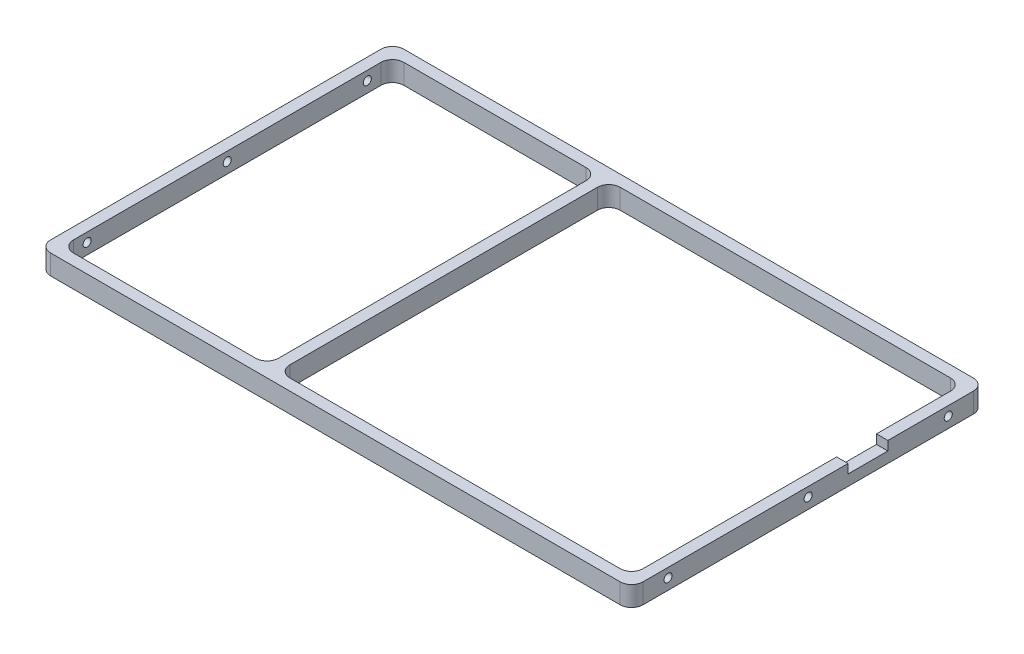
SolidWorks part; units mm, degrees
material "Delrin 2700 NC010, Low Viscosity Acetal Copolymer (SS)"
ref_plane "Front Plane" through (0, 0, 0) normal (0, 0, 1) x (1, 0, 0)
ref_plane "Top Plane" through (0, 0, 0) normal (0, 1, 0) x (1, 0, 0)
ref_plane "Right Plane" through (0, 0, 0) normal (1, 0, 0) x (0, 0, -1)
sketch "Sketch1" plane through (0, 0, 0) normal (0, 1, 0) x (1, 0, 0)
  line L1 (-165.1, -98.425) -> (165.1, -98.425)
  line L2 (-165.1, -98.425) -> (-165.1, 98.425)
  line L3 (-165.1, 98.425) -> (165.1, 98.425)
  line L4 (165.1, -98.425) -> (165.1, 98.425)
  line L5 (-165.1, -98.425) -> (165.1, 98.425) construction
  line L6 (-165.1, 98.425) -> (165.1, -98.425) construction
  point P0 (0, 0)
  dimension "D1" = 330.2
  dimension "D2" = 196.85
extrude "Boss-Extrude1" add sketch "Sketch1" along normal blind 11.1125
sketch "Sketch3" plane through (0, 11.1125, 0) normal (0, 1, 0) x (1, 0, 0)
  line L0 (-165.1, 98.425) -> (-165.1, -98.425) construction
  line L1 (-158.75, -92.075) -> (158.75, -92.075)
  line L2 (-158.75, -92.075) -> (-158.75, 92.075)
  line L3 (-158.75, 92.075) -> (158.75, 92.075)
  line L4 (158.75, -92.075) -> (158.75, 92.075)
  line L5 (-158.75, -92.075) -> (158.75, 92.075) construction
  line L6 (-158.75, 92.075) -> (158.75, -92.075) construction
  line L7 (165.1, 98.425) -> (-165.1, 98.425) construction
  point P0 (0, 0)
  dimension "D1" = 6.35
  dimension "D2" = 6.35
extrude "Cut-Extrude1" cut sketch "Sketch3" against normal through all
fillet "Fillet1" radius 6.35 8 edges at (158.75, 5.5562, -92.075) (165.1, 5.5562, -98.425) (158.75, 5.5562, 92.075) (165.1, 5.5562, 98.425) (-158.75, 5.5562, 92.075) (-165.1, 5.5562, 98.425) (-165.1, 5.5562, -98.425) (-158.75, 5.5562, -92.075)
sketch "Sketch4" plane through (0, 0, -92.075) normal (0, 0, 1) x (1, 0, 0)
  line L0 (152.4, 11.1125) -> (-152.4, 11.1125) construction
  line L1 (-44.45, 11.1125) -> (-38.1, 11.1125)
  line L2 (-44.45, 11.1125) -> (-44.45, 0)
  line L3 (-44.45, 0) -> (-38.1, 0)
  line L4 (-38.1, 11.1125) -> (-38.1, 0)
  line L5 (152.4, 0) -> (-152.4, 0) construction
  line L6 (-165.1, 11.1125) -> (-165.1, 0) construction
  dimension "D1" = 6.35
  dimension "D2" = 127
extrude "Boss-Extrude2" add sketch "Sketch4" along normal up to surface (184.15 mm away) up to face at (0, 5.5562, 92.075)
fillet "Fillet2" radius 6.35 4 edges at (-44.45, 5.5562, 92.075) (-38.1, 5.5562, 92.075) (-38.1, 5.5562, -92.075) (-44.45, 5.5562, -92.075)
hole_wizard "#8 Clearance Hole1" positions "Sketch7" profile "Sketch6" hole size "#8" standard "Ansi Inch"
sketch "Sketch7" plane through (-165.1, 0, 0) normal (-1, 0, 0) x (0, 0, 1)
  line L0 (-98.425, 0) -> (-98.425, 11.1125) construction
  line L1 (98.425, 11.1125) -> (98.425, 0) construction
  line L2 (-92.075, 11.1125) -> (92.075, 11.1125) construction
  point P0 (-78.105, 6.0325)
  point P1 (0, 6.0325)
  point P3 (78.105, 6.0325)
  dimension "D1" = 20.32
  dimension "D2" = 20.32
  dimension "D3" = 5.08
sketch "Sketch6" plane through (-165.1, 6.0325, -78.105) normal (0, 1, 0) x (0, 0, 1)
  line L0 (0, 0) -> (0, 127)
  line L1 (0, 127) -> (2.2479, 127)
  line L2 (2.2479, 127) -> (2.2479, 0)
  line L5 (2.2479, 0) -> (0, 0)
  line L11 (0, -6.35) -> (0, 107.95) construction
  dimension "Thru Hole Dia." = 4.4958
  dimension "Thru Hole Depth" = 127
mirror "Mirror1" about plane through (0, 0, 0) normal (1, 0, 0) of "#8 Clearance Hole1"
hole_wizard "#4-40 Tapped Hole1" positions "Sketch10" profile "Sketch9" tap size "#4-40" standard "Ansi Inch"
sketch "Sketch10" plane through (0, 0, 0) normal (0, -1, 0) x (1, 0, 0)
  line L0 (-170.1636, 94.615) -> (165.1, 94.615) construction
  line L2 (-158.75, 98.425) -> (158.75, 98.425) construction
  line L3 (-165.1, -92.075) -> (-165.1, 92.075) construction
  point P0 (-158.75, 94.615)
  point P1 (-101.6, 94.615)
  point P3 (-41.275, 94.615)
  point P5 (28.575, 94.615)
  point P7 (88.9, 94.615)
  point P9 (158.75, 94.615)
  dimension "D1" = 3.81
  dimension "D2" = 6.35
  dimension "D3" = 57.15
  dimension "D4" = 117.475
  dimension "D5" = 200.025
  dimension "D6" = 69.85
  dimension "D7" = 69.85
sketch "Sketch9" plane through (-158.75, 0, 94.615) normal (1, 0, 0) x (0, 0, -1)
  line L0 (0, 0) -> (0, 8.2992)
  line L1 (0, 8.2992) -> (1.1303, 7.62)
  line L2 (1.1303, 7.62) -> (1.1303, 0)
  line L5 (1.1303, 0) -> (0, 0)
  line L10 (0, 8.2992) -> (-1.1303, 7.62) construction
  line L11 (0, -6.35) -> (0, 107.95) construction
  dimension "Tap Drill Dia." = 2.2606
  dimension "Tap Drill Depth" = 7.62
  dimension "Drill Angle" = 118
cosmetic thread "Hole Thread1"
cosmetic thread "Hole Thread2"
cosmetic thread "Hole Thread3"
cosmetic thread "Hole Thread4"
cosmetic thread "Hole Thread5"
cosmetic thread "Hole Thread6"
mirror "Mirror2" about plane through (0, 0, 0) normal (0, 0, 1) of "#4-40 Tapped Hole1"
hole_wizard "#4-40 Tapped Hole2" positions "Sketch12" profile "Sketch11" tap size "#4-40" standard "Ansi Inch"
sketch "Sketch12" plane through (0, 0, 0) normal (0, -1, 0) x (1, 0, 0)
  line L0 (-165.1, -92.075) -> (-165.1, 92.075) construction
  line L1 (-158.75, 98.425) -> (158.75, 98.425) construction
  line L2 (158.75, -98.425) -> (-158.75, -98.425) construction
  point P0 (-161.29, 47.625)
  point P3 (-161.29, -47.625)
  dimension "D1" = 3.81
  dimension "D2" = 50.8
  dimension "D3" = 50.8
sketch "Sketch11" plane through (-161.29, 0, 47.625) normal (1, 0, 0) x (0, 0, -1)
  line L0 (0, 0) -> (0, 8.2992)
  line L1 (0, 8.2992) -> (1.1303, 7.62)
  line L2 (1.1303, 7.62) -> (1.1303, 0)
  line L5 (1.1303, 0) -> (0, 0)
  line L10 (0, 8.2992) -> (-1.1303, 7.62) construction
  line L11 (0, -6.35) -> (0, 107.95) construction
  dimension "Tap Drill Dia." = 2.2606
  dimension "Tap Drill Depth" = 7.62
  dimension "Drill Angle" = 118
cosmetic thread "Hole Thread7"
cosmetic thread "Hole Thread9"
pattern_linear "LPattern1" count 2 spacing 120.015 along (1, 0, 0) of "#4-40 Tapped Hole2"
mirror "Mirror3" about plane through (0, 0, 0) normal (1, 0, 0) of "#4-40 Tapped Hole2"
sketch "Sketch13" plane through (165.1, 0, 0) normal (1, 0, 0) x (0, 0, -1)
  line L1 (-92.075, 11.1125) -> (92.075, 11.1125) construction
  line L2 (22.225, 11.1125) -> (44.45, 11.1125)
  line L3 (22.225, 11.1125) -> (22.225, 6.0325)
  line L4 (22.225, 6.0325) -> (44.45, 6.0325)
  line L5 (44.45, 11.1125) -> (44.45, 6.0325)
  line L6 (98.425, 11.1125) -> (98.425, 0) construction
  dimension "D1" = 5.08
  dimension "D2" = 53.975
  dimension "D3" = 22.225
extrude "Cut-Extrude2" cut sketch "Sketch13" against normal up to next
